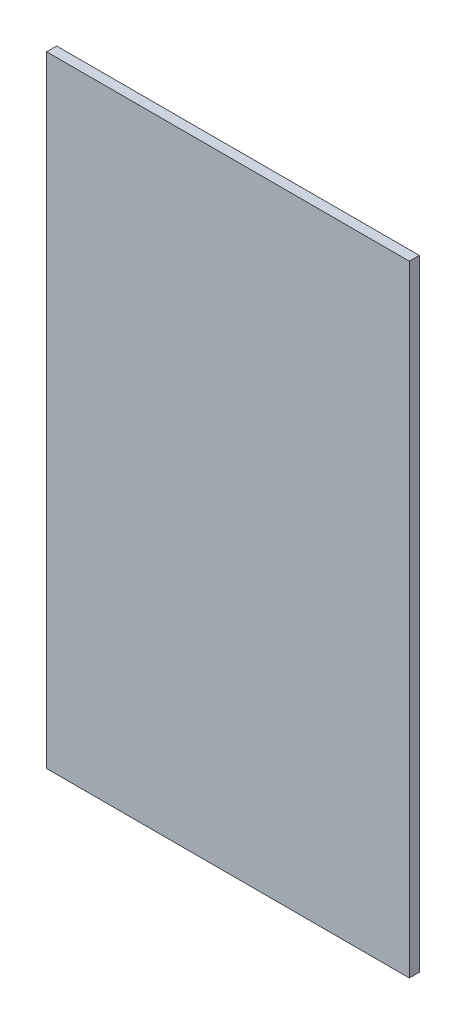
SolidWorks part; units mm, degrees
ref_plane "Front Plane" through (0, 0, 0) normal (0, 0, 1) x (1, 0, 0)
ref_plane "Top Plane" through (0, 0, 0) normal (0, 1, 0) x (1, 0, 0)
ref_plane "Right Plane" through (0, 0, 0) normal (1, 0, 0) x (0, 0, -1)
sketch "Sketch1" plane through (0, 0, 0) normal (0, 0, 1) x (1, 0, 0)
  line L1 (0, 0) -> (460.1228, 0)
  line L2 (0, 0) -> (0, 787.4)
  line L3 (0, 787.4) -> (460.1228, 787.4)
  line L4 (460.1228, 0) -> (460.1228, 787.4)
  dimension "D1" = 787.4
extrude "Boss-Extrude1" add sketch "Sketch1" along normal blind 12.7
